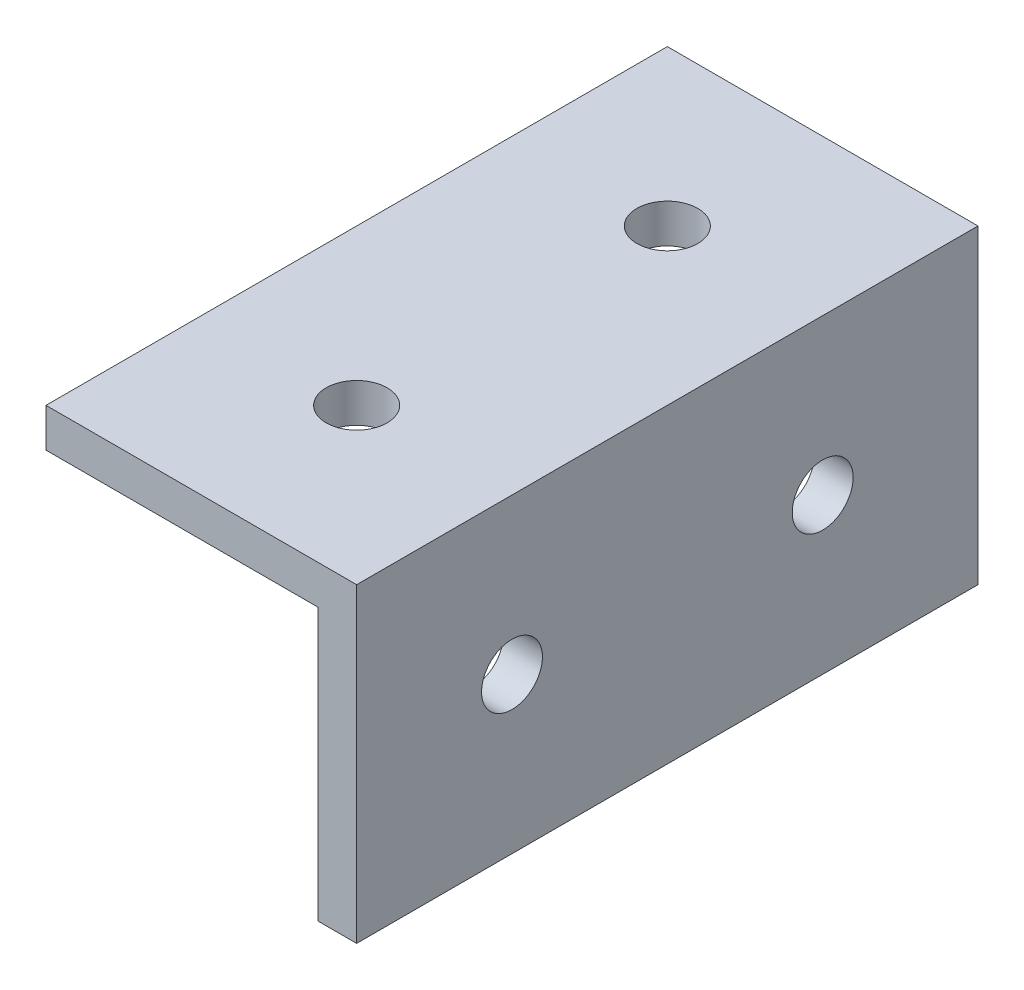
SolidWorks part; units mm, degrees
ref_plane "Front Plane" through (0, 0, 0) normal (1, 0, 0) x (0, 1, 0)
ref_plane "Top Plane" through (0, 0, 0) normal (0, 0, 1) x (0, 1, 0)
ref_plane "Right Plane" through (0, 0, 0) normal (0, 1, 0) x (-1, 0, 0)
sketch "Sketch1" plane through (0, 0, 0) normal (0, 0, 1) x (0, 1, 0)
  line L0 (12.7, 12.7) -> (12.7, -12.7)
  line L1 (-12.7, -12.7) -> (12.7, -12.7) construction
  line L2 (-12.7, -12.7) -> (-12.7, 12.7) construction
  line L3 (-12.7, 12.7) -> (12.7, 12.7) construction
  line L4 (12.7, -12.7) -> (12.7, 12.7) construction
  line L5 (-12.7, -12.7) -> (12.7, 12.7) construction
  line L6 (-12.7, 12.7) -> (12.7, -12.7) construction
  line L7 (12.7, -12.7) -> (-12.7, -12.7)
  line L8 (-12.7, -12.7) -> (-12.7, -9.525)
  line L9 (9.525, -9.525) -> (9.525, 12.7)
  line L10 (9.525, 12.7) -> (12.7, 12.7)
  line L11 (-12.7, -9.525) -> (9.525, -9.525)
  point P0 (0, 0)
  dimension "D1" = 25.4
  dimension "D2" = 25.4
  dimension "D3" = 3.175
extrude "Boss-Extrude1" add sketch "Sketch1" along normal blind 50.8
sketch "Sketch2" plane through (0, 12.7, 0) normal (0, 1, 0) x (-1, 0, 0)
  line L0 (-12.7, 50.8) -> (12.7, 50.8) construction
  line L1 (-12.7, 50.8) -> (-12.7, 0) construction
  point P0 (0, 38.1)
  point P1 (0, 12.7)
  dimension "D1" = 25.4
  dimension "D2" = 12.7
  dimension "D3" = 12.7
hole_wizard "#9 (0.196) Diameter Hole1" positions "Sketch2" profile "Sketch3" hole size "#9" standard "ANSI Inch" end condition through all
sketch "Sketch3" plane through (0, 12.7, 38.1) normal (1, 0, 0) x (0, 0, 1)
  line L0 (0, 0) -> (0, 25.4)
  line L1 (0, 25.4) -> (2.4892, 25.4)
  line L2 (2.4892, 25.4) -> (2.4892, 0)
  line L5 (2.4892, 0) -> (0, 0)
  line L11 (0, -6.35) -> (0, 107.95) construction
  dimension "Thru Hole Dia." = 4.9784
  dimension "Thru Hole Depth" = 25.4
sketch "Sketch4" plane through (12.7, 0, 0) normal (1, 0, 0) x (0, 1, 0)
  line L0 (-12.7, 50.8) -> (12.7, 50.8) construction
  line L1 (12.7, 50.8) -> (12.7, 0) construction
  point P0 (0, 38.1)
  point P1 (0, 12.7)
  point P6 (0, 0)
  dimension "D1" = 25.4
  dimension "D2" = 12.7
  dimension "D3" = 12.7
hole_wizard "#9 (0.196) Diameter Hole2" positions "Sketch4" profile "Sketch5" hole size "#9" standard "ANSI Inch" end condition through all
sketch "Sketch5" plane through (12.7, 0, 38.1) normal (0, 1, 0) x (0, 0, -1)
  line L0 (0, 0) -> (0, 25.4)
  line L1 (0, 25.4) -> (2.4892, 25.4)
  line L2 (2.4892, 25.4) -> (2.4892, 0)
  line L5 (2.4892, 0) -> (0, 0)
  line L11 (0, -6.35) -> (0, 107.95) construction
  dimension "Thru Hole Dia." = 4.9784
  dimension "Thru Hole Depth" = 25.4
